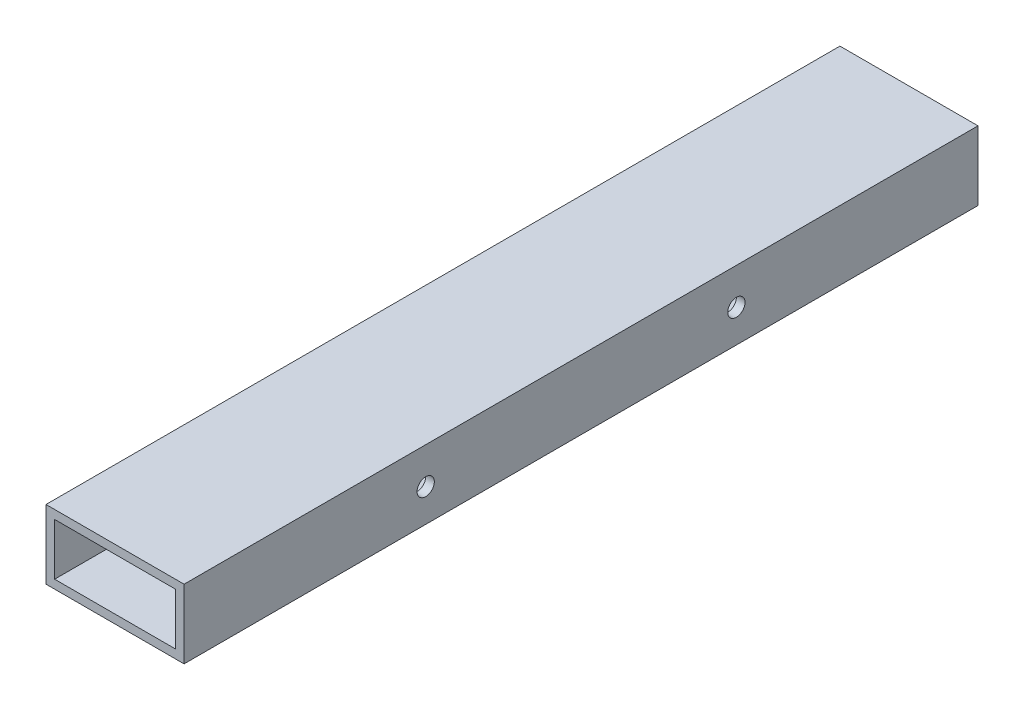
SolidWorks part; units mm, degrees
ref_plane "Front Plane" through (0, 0, 0) normal (0, 0, 1) x (1, 0, 0)
ref_plane "Top Plane" through (0, 0, 0) normal (0, 1, 0) x (1, 0, 0)
ref_plane "Right Plane" through (0, 0, 0) normal (1, 0, 0) x (0, 0, -1)
sketch "Sketch1" plane through (0, 0, 0) normal (0, 0, 1) x (1, 0, 0)
  line L0 (3.175, 22.225) -> (47.625, 22.225)
  line L1 (0, 0) -> (50.8, 0)
  line L2 (0, 0) -> (0, 25.4)
  line L3 (0, 25.4) -> (50.8, 25.4)
  line L4 (50.8, 0) -> (50.8, 25.4)
  line L5 (47.625, 3.175) -> (47.625, 22.225)
  line L6 (3.175, 3.175) -> (47.625, 3.175)
  line L7 (3.175, 3.175) -> (3.175, 22.225)
  dimension "D2" = 50.8
  dimension "D3" = 25.4
  dimension "D1" = 3.175
extrude "Boss-Extrude1" add sketch "Sketch1" along normal blind 292.1
sketch "Sketch2" plane through (50.8, 0, 0) normal (1, 0, 0) x (0, 0, -1)
  line L0 (-146.05, 25.4) -> (-146.05, 12.0268) construction
  line L1 (-292.1, 25.4) -> (0, 25.4) construction
  line L2 (-146.05, 12.0268) -> (-203.2, 12.0268) construction
  line L3 (-146.05, 12.0268) -> (-88.9, 12.0268) construction
  circle A0 centre (-203.2, 12.0268) radius 3.175
  circle A1 centre (-88.9, 12.0268) radius 3.175
  dimension "D3" = 6.35
  dimension "D1" = 13.3732
  dimension "D2" = 57.15
extrude "Cut-Extrude1" cut sketch "Sketch2" against normal through all both
